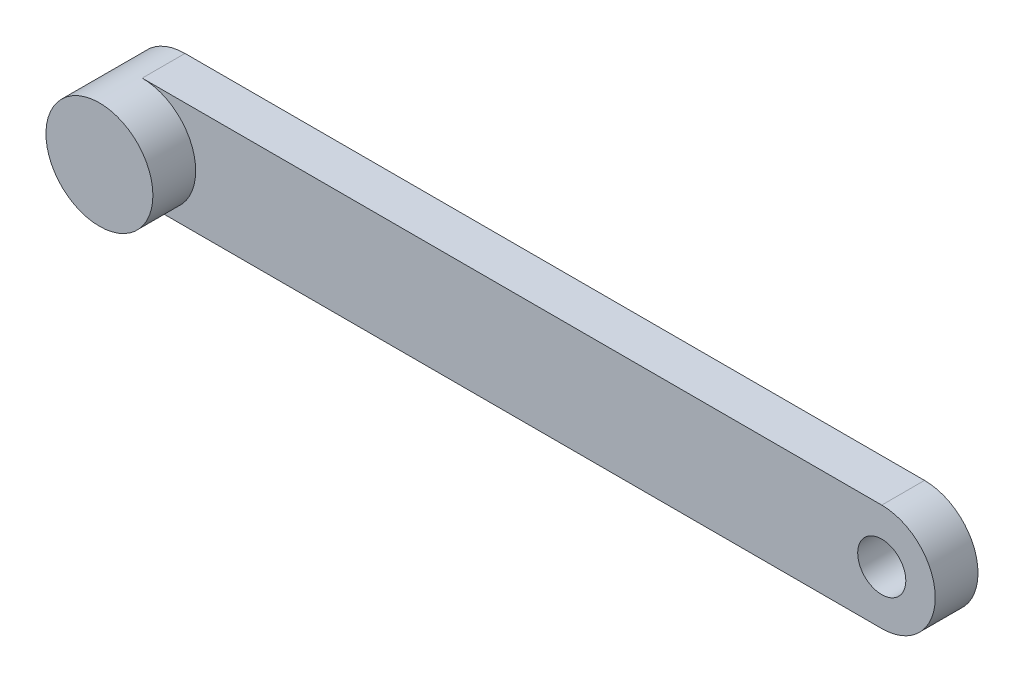
SolidWorks part; units mm, degrees
ref_plane "Front Plane" through (0, 0, 0) normal (0, 0, 1) x (1, 0, 0)
ref_plane "Top Plane" through (0, 0, 0) normal (0, 1, 0) x (1, 0, 0)
ref_plane "Right Plane" through (0, 0, 0) normal (1, 0, 0) x (0, 0, -1)
sketch "Sketch1" plane through (0, 0, 0) normal (0, 0, 1) x (1, 0, 0)
  line L0 (0, 0) -> (69.15, 0) construction
  line L1 (0, 5) -> (69.15, 5)
  line L2 (0, -5) -> (69.15, -5)
  arc A0 (0, 5) -> (0, -5) centre (0, 0) ccw
  arc A1 (69.15, -5) -> (69.15, 5) centre (69.15, 0) ccw
  point P3 (34.575, 0)
  dimension "D1" = 10
  dimension "D2" = 69.15
extrude "Boss-Extrude1" add sketch "Sketch1" along normal mid plane 4
sketch "Sketch2" plane through (0, 0, 2) normal (0, 0, 1) x (1, 0, 0)
  circle A0 centre (0, 0) radius 5
  dimension "D1" = 10
extrude "Boss-Extrude2" add sketch "Sketch2" along normal mid plane 8
hole_wizard "M4 Clearance Hole1" positions "Sketch3" profile "Sketch4" hole size "M4" standard "ANSI Metric" end condition through all
sketch "Sketch3" plane through (0, 0, -2) normal (0, 0, -1) x (-1, 0, 0)
  point P0 (-69.15, 0)
sketch "Sketch4" plane through (69.15, 0, -2) normal (1, 0, 0) x (0, 1, 0)
  line L0 (0, 0) -> (0, 8)
  line L1 (0, 8) -> (2.25, 8)
  line L2 (2.25, 8) -> (2.25, 0)
  line L5 (2.25, 0) -> (0, 0)
  line L11 (0, -6.35) -> (0, 107.95) construction
  dimension "Thru Hole Dia." = 4.5
  dimension "Thru Hole Depth" = 8
sketch "Sketch5" plane through (0, 0, 2) normal (0, 0, 1) x (1, 0, 0)
  point P0 (0, 0)
  point P1 (15.4236, 25.779)
